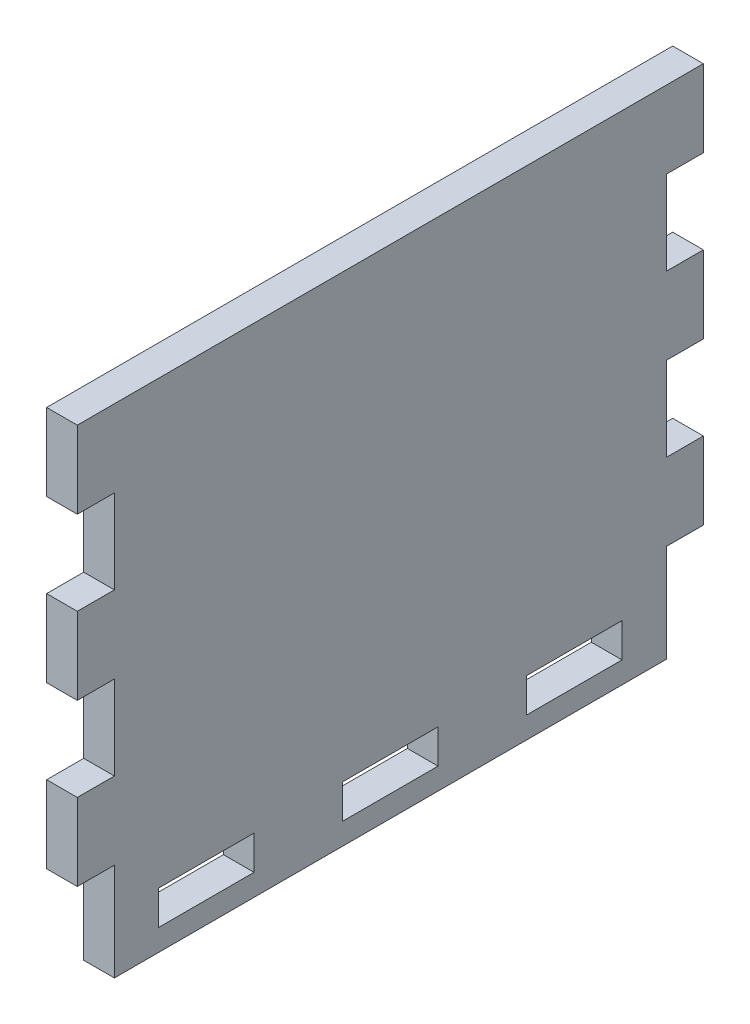
SolidWorks part; units mm, degrees
material "ABS"
ref_plane "Front Plane" through (0, 0, 0) normal (0, 0, 1) x (1, 0, 0)
ref_plane "Top Plane" through (0, 0, 0) normal (0, 1, 0) x (1, 0, 0)
ref_plane "Right Plane" through (0, 0, 0) normal (1, 0, 0) x (0, 0, -1)
sketch "Sketch2" plane through (-44.7458, 0, 0) normal (-1, 0, 0) x (0, 0, 1)
  line L0 (91.7954, 28.4905) -> (91.7954, 40.3087) construction
  line L1 (91.7954, 40.3087) -> (86.3598, 40.3087) construction
  line L2 (86.3598, 40.3087) -> (86.3598, 28.4905) construction
  line L3 (86.3598, 28.4905) -> (91.7954, 28.4905) construction
  line L4 (91.7954, 4.8542) -> (91.7954, 16.6724) construction
  line L5 (91.7954, 16.6724) -> (86.3598, 16.6724) construction
  line L6 (86.3598, 16.6724) -> (86.3598, 4.8542) construction
  line L7 (86.3598, 4.8542) -> (91.7954, 4.8542) construction
  line L8 (91.7954, -18.7822) -> (91.7954, -6.964) construction
  line L9 (91.7954, -6.964) -> (86.3598, -6.964) construction
  line L10 (86.3598, -6.964) -> (86.3598, -18.7822) construction
  line L11 (86.3598, -18.7822) -> (91.7954, -18.7822) construction
  line L12 (79.6161, -24.9413) -> (66.1287, -24.9413) construction
  line L13 (5.4356, 40.0587) -> (0, 40.0587)
  line L14 (66.1287, -29.4371) -> (79.6161, -29.4371) construction
  line L15 (0, 40.0587) -> (0, 28.7405)
  line L16 (52.6414, -29.4371) -> (66.1287, -29.4371) construction
  line L17 (66.1287, -29.4371) -> (66.1287, -24.9413) construction
  line L18 (66.1287, -24.9413) -> (52.6414, -24.9413) construction
  line L19 (0, 28.7405) -> (5.4356, 28.7405)
  line L20 (52.6414, -24.9413) -> (39.154, -24.9413) construction
  line L21 (5.4356, 28.7405) -> (5.4356, 16.4224)
  line L22 (39.154, -29.4371) -> (52.6414, -29.4371) construction
  line L23 (52.6414, -29.4371) -> (52.6414, -24.9413) construction
  line L24 (25.6666, -29.4371) -> (39.154, -29.4371) construction
  line L25 (39.154, -29.4371) -> (39.154, -24.9413) construction
  line L26 (39.154, -24.9413) -> (25.6666, -24.9413) construction
  line L27 (5.4356, 16.4224) -> (0, 16.4224)
  line L28 (25.6666, -24.9413) -> (12.1793, -24.9413) construction
  line L29 (0, 16.4224) -> (0, 5.1042)
  line L30 (12.1793, -29.4371) -> (25.6666, -29.4371) construction
  line L31 (25.6666, -29.4371) -> (25.6666, -24.9413) construction
  line L32 (5.4356, -29.4371) -> (12.1793, -29.4371) construction
  line L33 (12.1793, -29.4371) -> (12.1793, -24.9413) construction
  line L34 (12.1793, -24.9413) -> (5.4356, -24.9413) construction
  line L35 (5.4356, -24.9413) -> (5.4356, -29.4371) construction
  line L36 (0, -6.964) -> (0, -18.7822) construction
  line L37 (0, -18.7822) -> (5.4356, -18.7822) construction
  line L38 (5.4356, -18.7822) -> (5.4356, -6.964) construction
  line L39 (5.4356, -6.964) -> (0, -6.964) construction
  line L40 (0, 16.6724) -> (0, 4.8542) construction
  line L41 (0, 4.8542) -> (5.4356, 4.8542) construction
  line L42 (5.4356, 4.8542) -> (5.4356, 16.6724) construction
  line L43 (5.4356, 16.6724) -> (0, 16.6724) construction
  line L44 (0, 40.3087) -> (0, 28.4905) construction
  line L45 (0, 28.4905) -> (5.4356, 28.4905) construction
  line L46 (5.4356, 28.4905) -> (5.4356, 40.3087) construction
  line L47 (5.4356, 40.3087) -> (0, 40.3087) construction
  line L48 (91.7954, 28.4905) -> (91.7954, 40.3087) construction
  line L49 (91.7954, 40.3087) -> (86.3598, 40.3087) construction
  line L50 (86.3598, 40.3087) -> (86.3598, 28.4905) construction
  line L51 (86.3598, 28.4905) -> (91.7954, 28.4905) construction
  line L52 (91.7954, 4.8542) -> (91.7954, 16.6724) construction
  line L53 (91.7954, 16.6724) -> (86.3598, 16.6724) construction
  line L54 (86.3598, 16.6724) -> (86.3598, 4.8542) construction
  line L55 (86.3598, 4.8542) -> (91.7954, 4.8542) construction
  line L56 (91.7954, -18.7822) -> (91.7954, -6.964) construction
  line L57 (91.7954, -6.964) -> (86.3598, -6.964) construction
  line L58 (86.3598, -6.964) -> (86.3598, -18.7822) construction
  line L59 (86.3598, -18.7822) -> (91.7954, -18.7822) construction
  line L60 (79.6161, -24.9413) -> (66.1287, -24.9413) construction
  line L62 (66.1287, -29.4371) -> (79.6161, -29.4371) construction
  line L64 (52.6414, -29.4371) -> (66.1287, -29.4371) construction
  line L65 (66.1287, -29.4371) -> (66.1287, -24.9413) construction
  line L66 (66.1287, -24.9413) -> (52.6414, -24.9413) construction
  line L68 (52.6414, -24.9413) -> (39.154, -24.9413) construction
  line L70 (39.154, -29.4371) -> (52.6414, -29.4371) construction
  line L71 (52.6414, -29.4371) -> (52.6414, -24.9413) construction
  line L72 (25.6666, -29.4371) -> (39.154, -29.4371) construction
  line L73 (39.154, -29.4371) -> (39.154, -24.9413) construction
  line L74 (39.154, -24.9413) -> (25.6666, -24.9413) construction
  line L76 (25.6666, -24.9413) -> (12.1793, -24.9413) construction
  line L78 (12.1793, -29.4371) -> (25.6666, -29.4371) construction
  line L79 (25.6666, -29.4371) -> (25.6666, -24.9413) construction
  line L80 (5.4356, -29.4371) -> (12.1793, -29.4371) construction
  line L81 (12.1793, -29.4371) -> (12.1793, -24.9413) construction
  line L82 (12.1793, -24.9413) -> (5.4356, -24.9413) construction
  line L83 (5.4356, -24.9413) -> (5.4356, -29.4371) construction
  line L84 (0, -6.964) -> (0, -18.7822) construction
  line L85 (0, -18.7822) -> (5.4356, -18.7822) construction
  line L86 (5.4356, -18.7822) -> (5.4356, -6.964) construction
  line L87 (5.4356, -6.964) -> (0, -6.964) construction
  line L88 (0, 16.6724) -> (0, 4.8542) construction
  line L89 (0, 4.8542) -> (5.4356, 4.8542) construction
  line L90 (5.4356, 4.8542) -> (5.4356, 16.6724) construction
  line L91 (5.4356, 16.6724) -> (0, 16.6724) construction
  line L92 (0, 40.3087) -> (0, 28.4905) construction
  line L93 (0, 28.4905) -> (5.4356, 28.4905) construction
  line L94 (5.4356, 28.4905) -> (5.4356, 40.3087) construction
  line L95 (5.4356, 40.3087) -> (0, 40.3087) construction
  line L96 (0, 5.1042) -> (5.4356, 5.1042)
  line L97 (5.4356, 5.1042) -> (5.4356, -7.214)
  line L98 (5.4356, -7.214) -> (0, -7.214)
  line L99 (0, -7.214) -> (0, -18.5322)
  line L100 (79.6161, -29.4371) -> (86.3598, -29.4371)
  line L101 (86.3598, -29.4371) -> (86.3598, -24.9413)
  line L102 (86.3598, -24.9413) -> (79.6161, -24.9413)
  line L103 (79.6161, -24.9413) -> (79.6161, -29.4371)
  line L104 (79.6161, -29.4371) -> (86.3598, -29.4371) construction
  line L105 (86.3598, -29.4371) -> (86.3598, -24.9413) construction
  line L106 (86.3598, -24.9413) -> (79.6161, -24.9413) construction
  line L107 (79.6161, -24.9413) -> (79.6161, -29.4371) construction
  line L108 (0, -18.5322) -> (5.4356, -18.5322)
  line L109 (5.4356, -18.5322) -> (5.4356, -32.8621)
  line L110 (5.4356, -32.8621) -> (86.3598, -32.8621)
  line L111 (86.3598, -32.8621) -> (86.3598, -18.5322)
  line L112 (86.3598, -18.5322) -> (91.7954, -18.5322)
  line L113 (91.7954, -18.5322) -> (91.7954, -7.214)
  line L114 (91.7954, -7.214) -> (86.3598, -7.214)
  line L115 (86.3598, -7.214) -> (86.3598, 5.1042)
  line L116 (86.3598, 5.1042) -> (91.7954, 5.1042)
  line L117 (91.7954, 5.1042) -> (91.7954, 16.4224)
  line L118 (91.7954, 16.4224) -> (86.3598, 16.4224)
  line L119 (86.3598, 16.4224) -> (86.3598, 28.7405)
  line L120 (86.3598, 28.7405) -> (91.7954, 28.7405)
  line L121 (91.7954, 28.7405) -> (91.7954, 40.0587)
  line L122 (91.7954, 40.0587) -> (86.3598, 40.0587)
  line L123 (86.3598, 40.0587) -> (5.4356, 40.0587)
  line L124 (2.7178, 40.3087) -> (2.7178, 40.0587) construction
  line L125 (11.9293, -24.6913) -> (25.9166, -24.6913)
  line L126 (11.9293, -24.6913) -> (11.9293, -29.6871)
  line L127 (11.9293, -29.6871) -> (25.9166, -29.6871)
  line L128 (25.9166, -24.6913) -> (25.9166, -29.6871)
  line L129 (38.904, -24.6913) -> (52.8914, -24.6913)
  line L130 (38.904, -24.6913) -> (38.904, -29.6871)
  line L131 (38.904, -29.6871) -> (52.8914, -29.6871)
  line L132 (52.8914, -24.6913) -> (52.8914, -29.6871)
  line L133 (65.8787, -24.6913) -> (79.8661, -24.6913)
  line L134 (65.8787, -24.6913) -> (65.8787, -29.6871)
  line L135 (65.8787, -29.6871) -> (79.8661, -29.6871)
  line L136 (79.8661, -24.6913) -> (79.8661, -29.6871)
  line L137 (5.4356, -32.8621) -> (0, -32.8621) construction
  line L138 (2.7178, 28.7405) -> (2.7178, 28.4905) construction
  line L139 (18.923, -24.6913) -> (18.923, -24.9413) construction
  line L140 (2.7178, 16.6724) -> (2.7178, 16.4224) construction
  line L141 (25.6666, -27.1892) -> (25.9166, -27.1892) construction
  line L142 (2.7178, 5.1042) -> (2.7178, 4.8542) construction
  line L143 (18.923, -29.4371) -> (18.923, -29.6871) construction
  line L144 (2.7178, -6.964) -> (2.7178, -7.214) construction
  line L145 (12.1793, -27.1892) -> (11.9293, -27.1892) construction
  line L146 (2.7178, -18.5322) -> (2.7178, -18.7822) construction
  line L147 (39.154, -27.1892) -> (38.904, -27.1892) construction
  line L148 (66.1287, -27.1892) -> (65.8787, -27.1892) construction
  dimension "D2" = 0.25
  dimension "D1" = 0
extrude "Boss-Extrude1" add sketch "Sketch2" against normal offset from surface (4.4958 mm away) 0.25
